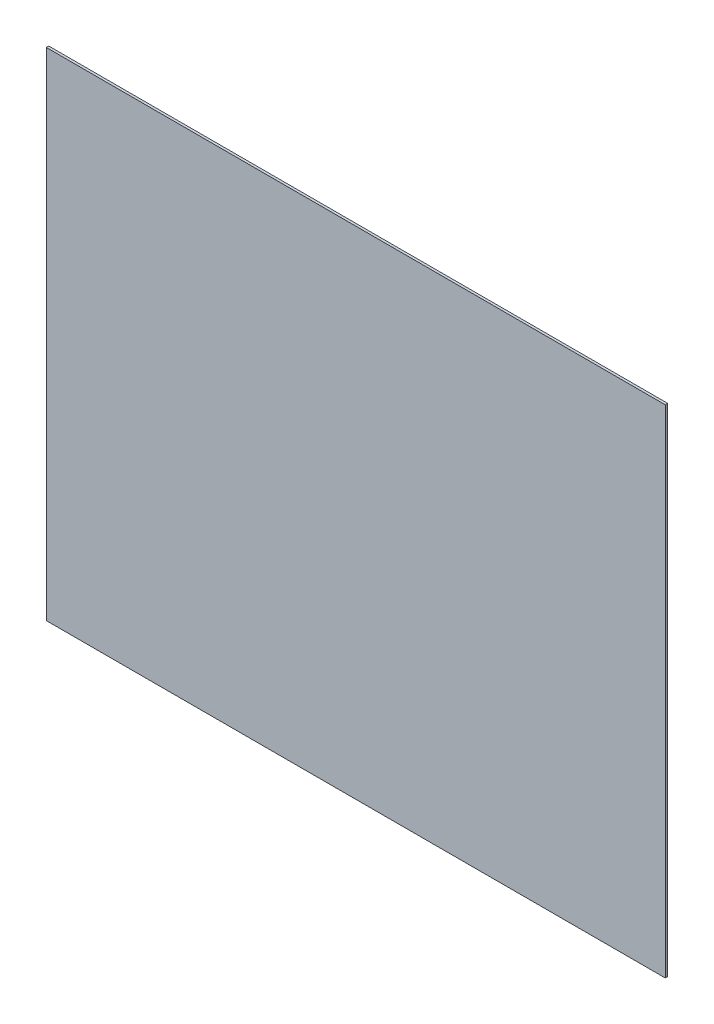
SolidWorks part; units mm, degrees
ref_plane "Front Plane" through (0, 0, 0) normal (0, 0, 1) x (1, 0, 0)
ref_plane "Top Plane" through (0, 0, 0) normal (0, 1, 0) x (1, 0, 0)
ref_plane "Right Plane" through (0, 0, 0) normal (1, 0, 0) x (0, 0, -1)
ref_plane "Plane1" through (0, 0, -405) normal (0, 0, -1) x (-1, 0, 0)
sketch "Sketch1" plane through (0, 0, -405) normal (0, 0, -1) x (-1, 0, 0)
  line L0 (-405, -370) -> (100, -370)
  line L1 (100, -370) -> (100, 35)
  line L2 (100, 35) -> (-405, 35)
  line L3 (-405, 35) -> (-405, -370)
  dimension "D1" = 505
  dimension "D2" = 405
extrude "Boss-Extrude1" add sketch "Sketch1" against normal blind 2
